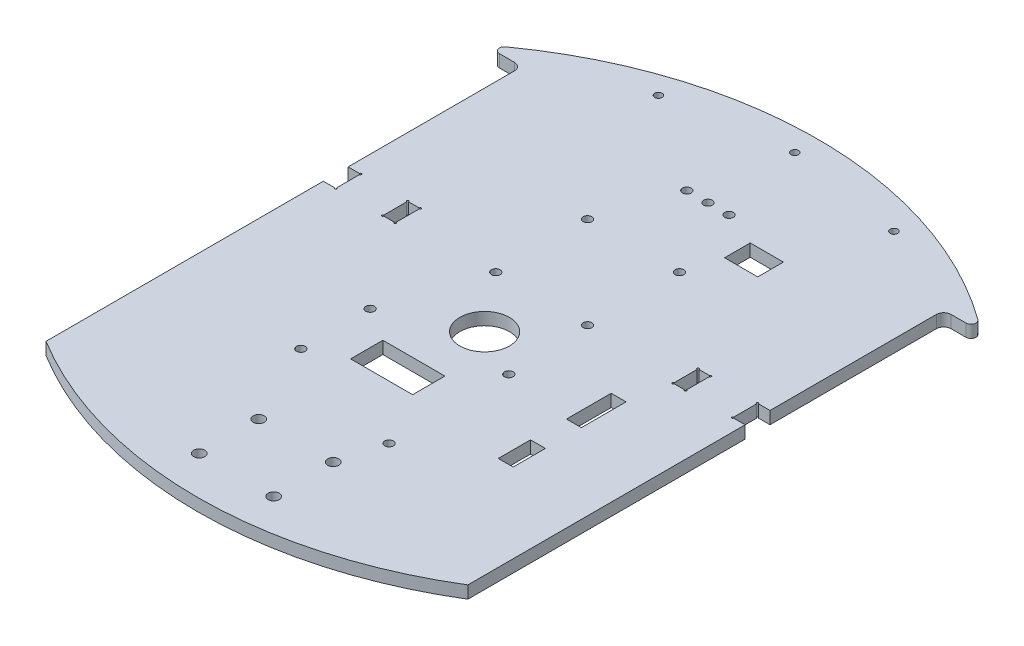
SolidWorks part; units mm, degrees
ref_plane "前视基准面" through (0, 0, 0) normal (0, 0, 1) x (1, 0, 0)
ref_plane "上视基准面" through (0, 0, 0) normal (0, 1, 0) x (1, 0, 0)
ref_plane "右视基准面" through (0, 0, 0) normal (1, 0, 0) x (0, 0, -1)
other "Configuration Table"
sketch "草图1" plane through (0, 0, 0) normal (0, 1, 0) x (1, 0, 0)
  line L0 (-93.9917, 100) -> (-88, 100)
  line L5 (-96.1127, -103.7335) -> (95.6694, 103.255) construction
  line L6 (-148.6945, 160.4845) -> (95.4767, -103.047) construction
  line L7 (93.9917, 100) -> (88, 100)
  line L8 (-85, 97) -> (-85, -91.7396)
  line L9 (85, 97) -> (85, -91.7396)
  arc A0 (-95.1603, 103.623) -> (95.1603, 103.623) centre (0, -28.5368) cw
  arc A1 (-85, -91.7396) -> (85, -91.7396) centre (0, 47.1729) ccw
  arc A2 (88, 100) -> (85, 97) centre (88, 97) ccw
  arc A3 (-88, 100) -> (-85, 97) centre (-88, 97) cw
  arc A4 (93.9917, 100) -> (95.1603, 103.623) centre (93.9917, 102) ccw
  arc A5 (-93.9917, 100) -> (-95.1603, 103.623) centre (-93.9917, 102) cw
  point P0 (0, 0)
  point P17 (85, 100)
  point P20 (-85, 100)
  point P23 (100, 100)
  point P26 (-100, 100)
  point P27 (0, -115.6819)
  point P28 (0, 134.3181)
  dimension "D5" = 3
  dimension "D6" = 2
  dimension "D7" = 2
  dimension "D8" = 162.8548
  dimension "D1" = 85
  dimension "D2" = 85
  dimension "D3" = 15
  dimension "D4" = 15
  dimension "D9" = 250
  dimension "D10" = 100
extrude "凸台-拉伸1" add sketch "草图1" along normal blind 5
sketch "草图3" plane through (0, 5, 0) normal (0, 1, 0) x (1, 0, 0)
  line L0 (-85, 20) -> (-80.4, 20)
  line L1 (-85, 97) -> (-85, -91.7396) construction
  line L2 (-80, 20.4) -> (-80, 29.6)
  line L3 (-80.4, 30) -> (-85, 30)
  line L4 (-85, 30) -> (-85, 20)
  line L5 (-61, 29.6) -> (-61, 20.4)
  line L6 (-60.6, 20) -> (-56.4, 20)
  line L7 (-56, 20.4) -> (-56, 29.6)
  line L8 (-56.4, 30) -> (-60.6, 30)
  line L9 (0, -2.75) -> (0, 2.75) construction
  line L10 (61, 29.6) -> (61, 20.4)
  line L11 (60.6, 20) -> (56.4, 20)
  line L12 (56, 20.4) -> (56, 29.6)
  line L13 (56.4, 30) -> (60.6, 30)
  line L14 (85, 30) -> (85, 20)
  line L15 (85, 20) -> (80.4, 20)
  line L16 (80, 20.4) -> (80, 29.6)
  line L17 (80.4, 30) -> (85, 30)
  line L18 (-47.4455, 117.4854) -> (0, -28.5368) construction
  line L23 (0, -28.5368) -> (47.4455, 117.4854) construction
  line L24 (0, 125) -> (0, -28.5368) construction
  line L29 (22.5607, 74.1346) -> (35.9174, 74.1346)
  line L30 (22.5607, 74.1346) -> (22.5607, 84.4753)
  line L31 (22.5607, 84.4753) -> (35.9174, 84.4753)
  line L32 (35.9174, 74.1346) -> (35.9174, 84.4753)
  line L33 (22.5607, 74.1346) -> (35.9174, 84.4753) construction
  line L34 (22.5607, 84.4753) -> (35.9174, 74.1346) construction
  circle A1 centre (15, -100) radius 2.25
  circle A2 centre (-15, -100) radius 2.25
  circle A3 centre (-15, -76) radius 2.25
  circle A4 centre (15, -76) radius 2.25
  circle A5 centre (-18.5, 60) radius 1.75
  circle A6 centre (18.5, 60) radius 1.75
  circle A7 centre (18.5, 23) radius 1.75
  circle A8 centre (-18.5, 23) radius 1.75
  circle A9 centre (-8.5, 90) radius 1.75
  circle A10 centre (0, 90) radius 1.75
  circle A11 centre (8.5, 90) radius 1.75
  circle A12 centre (0, 125) radius 1.5
  circle A13 centre (19.76, -10) radius 1.75
  circle A14 centre (19.76, -58.26) radius 1.75
  circle A15 centre (-31.04, -15.08) radius 1.75
  circle A16 centre (-31.04, -43.02) radius 1.75
  arc A17 (-80, 29.6) -> (-80.4, 30) centre (-80, 30) ccw
  arc A18 (-80.4, 20) -> (-80, 20.4) centre (-80, 20) ccw
  arc A19 (-60.6, 30) -> (-61, 29.6) centre (-61, 30) ccw
  arc A20 (-61, 20.4) -> (-60.6, 20) centre (-61, 20) ccw
  arc A21 (-56, 29.6) -> (-56.4, 30) centre (-56, 30) ccw
  arc A22 (-56.4, 20) -> (-56, 20.4) centre (-56, 20) ccw
  arc A23 (61, 29.6) -> (60.6, 30) centre (61, 30) ccw
  arc A24 (56.4, 30) -> (56, 29.6) centre (56, 30) ccw
  arc A25 (56, 20.4) -> (56.4, 20) centre (56, 20) ccw
  arc A26 (60.6, 20) -> (61, 20.4) centre (61, 20) ccw
  arc A27 (80.4, 30) -> (80, 29.6) centre (80, 30) ccw
  arc A28 (80, 20.4) -> (80.4, 20) centre (80, 20) ccw
  circle A33 centre (0, -28.5368) radius 153.5368 construction
  circle A34 centre (47.4455, 117.4854) radius 1.5
  circle A35 centre (-47.4455, 117.4854) radius 1.5
  point P50 (0, 86.877)
  point P53 (29.239, 79.3049)
  dimension "D8" = 3
  dimension "D9" = 4.5
  dimension "D14" = 3.5
  dimension "D19" = 3.5
  dimension "D23" = 3
  dimension "D26" = 3.5
  dimension "D29" = 3.5
  dimension "D35" = 0.8
  dimension "D10" = 3
  dimension "D1" = 5
  dimension "D2" = 10
  dimension "D3" = 20
  dimension "D4" = 5
  dimension "D5" = 10
  dimension "D6" = 19
  dimension "D7" = 0
  dimension "D11" = 18
  dimension "D15" = 18
  dimension "D16" = 24
  dimension "D20" = 30
  dimension "D30" = 5.08
  dimension "D31" = 50.8
  dimension "D32" = 50.8
  dimension "D34" = 27.94
  dimension "D12" = 2
  dimension "D13" = 2
  dimension "D17" = 2
  dimension "D18" = 2
  dimension "D22" = 3
  dimension "D28" = 2
extrude "切除-拉伸1" cut sketch "草图3" against normal blind 5
sketch "草图4" plane through (0, 5, 0) normal (0, 1, 0) x (1, 0, 0)
  line L1 (47, 4) -> (53, 4)
  line L2 (47, 4) -> (47, -14)
  line L3 (47, -14) -> (53, -14)
  line L4 (53, 4) -> (53, -14)
  line L5 (47, 4) -> (53, -14) construction
  line L6 (47, -14) -> (53, 4) construction
  line L7 (53, -28.5) -> (47, -28.5)
  line L8 (53, -28.5) -> (53, -41.5)
  line L9 (53, -41.5) -> (47, -41.5)
  line L10 (47, -28.5) -> (47, -41.5)
  line L11 (53, -28.5) -> (47, -41.5) construction
  line L12 (53, -41.5) -> (47, -28.5) construction
  line L13 (-17.5, -23.5) -> (7.5, -23.5)
  line L14 (-17.5, -23.5) -> (-17.5, -36.5)
  line L15 (-17.5, -36.5) -> (7.5, -36.5)
  line L16 (7.5, -23.5) -> (7.5, -36.5)
  line L17 (-17.5, -23.5) -> (7.5, -36.5) construction
  line L18 (-17.5, -36.5) -> (7.5, -23.5) construction
  circle A0 centre (0, 0) radius 10
  point P3 (50, -5)
  point P8 (50, -35)
  point P13 (-5, -30)
  point P18 (0, 0)
  dimension "D1" = 20
  dimension "D2" = 18
  dimension "D3" = 6
  dimension "D4" = 13
  dimension "D5" = 6
  dimension "D6" = 50
  dimension "D7" = 5
  dimension "D8" = 35
  dimension "D9" = 50
  dimension "D10" = 30
  dimension "D11" = 5
  dimension "D12" = 25
  dimension "D13" = 13
extrude "切除-拉伸2" cut sketch "草图4" against normal through all
